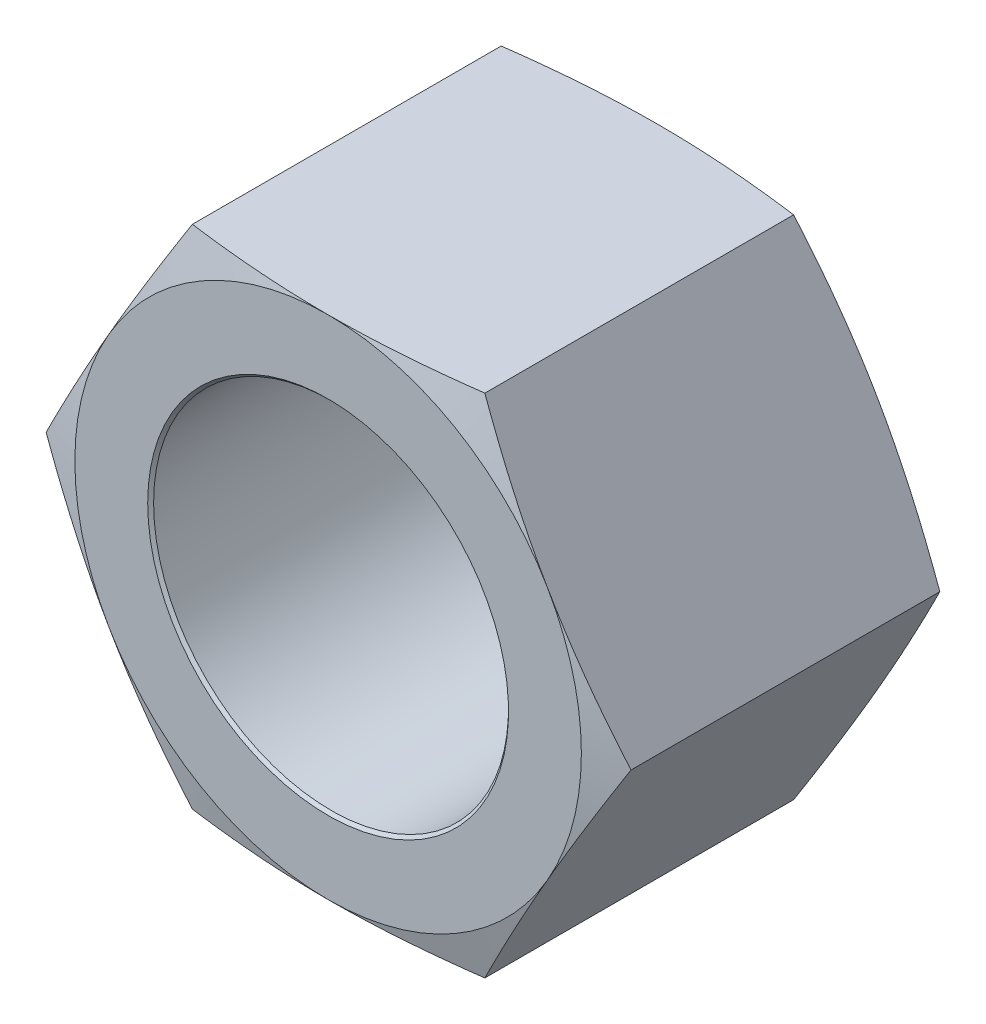
SolidWorks part; units mm, degrees
ref_plane "基准面1" through (0, 0, 0) normal (0, 0, 1) x (1, 0, 0)
ref_plane "基准面2" through (0, 0, 0) normal (0, 1, 0) x (1, 0, 0)
ref_plane "基准面3" through (0, 0, 0) normal (1, 0, 0) x (0, 0, -1)
sketch "尺寸草图" plane through (0, 0, 0) normal (0, 0, 1) x (1, 0, 0)
  line L0 (0, 0) -> (24.1005, 0)
  point P3 (24, 0)
  point P4 (1.5, 0)
  point P5 (39.55, 0)
  point P6 (22.3, 0)
  point P7 (6.4, 0)
  point P8 (36, 0)
  dimension "D" = 24
  dimension "e" = 39.55
  dimension "P1" = 1.5
  dimension "m" = 22.3
  dimension "mw" = 6.4
  dimension "s" = 36
sketch "草图1" plane through (0, 0, 0) normal (0, 0, 1) x (1, 0, 0)
  line L0 (-26.8088, 0) -> (37.1748, 0) construction
  line L1 (0, 25.0215) -> (0, -25.0215) construction
  line L3 (9.8875, 17.1257) -> (-9.8875, 17.1257)
  line L4 (-9.8875, 17.1257) -> (-19.775, 0)
  line L5 (-19.775, 0) -> (-9.8875, -17.1257)
  line L6 (-9.8875, -17.1257) -> (9.8875, -17.1257)
  line L7 (9.8875, -17.1257) -> (19.775, 0)
  line L8 (19.775, 0) -> (9.8875, 17.1257)
  circle A0 centre (0, 0) radius 17.1257 construction
  circle A1 centre (0, 0) radius 12
  dimension "D" = 24
  dimension "e" = 39.55
extrude "基体-拉伸" add sketch "草图1" along normal blind 22.3
cosmetic thread "装饰螺纹线1" parameters "D2"=25.2
sketch "草图2" plane through (0, 0, 0) normal (0, 0, -1) x (-1, 0, 0)
  line L0 (-9.8875, 17.1257) -> (9.8875, 17.1257) construction
  circle A0 centre (0, 0) radius 17.1257
  circle A1 centre (0, 0) radius 12 construction
extrude "切除-拉伸1" cut sketch "草图2" against normal blind 38 draft 75 flip side to cut
sketch "草图3" plane through (0, 0, 22.3) normal (0, 0, 1) x (1, 0, 0)
  line L0 (19.775, 0) -> (9.8875, 17.1257) construction
  circle A0 centre (0, 0) radius 17.1257
extrude "切除-拉伸2" cut sketch "草图3" against normal blind 38 draft 75 flip side to cut
chamfer "倒角1" distance 0.2 angle 45 2 edges at (12, 0, 0) (12, 0, 22.3)
equation "\"e@草图1\" = \"e@尺寸草图\""
equation "\"D@草图1\" = \"D@尺寸草图\""
equation "\"m@基体-拉伸\" = \"m@尺寸草图\""
equation "\"D2@装饰螺纹线1\" = 1.05 * \"D@尺寸草图\""
